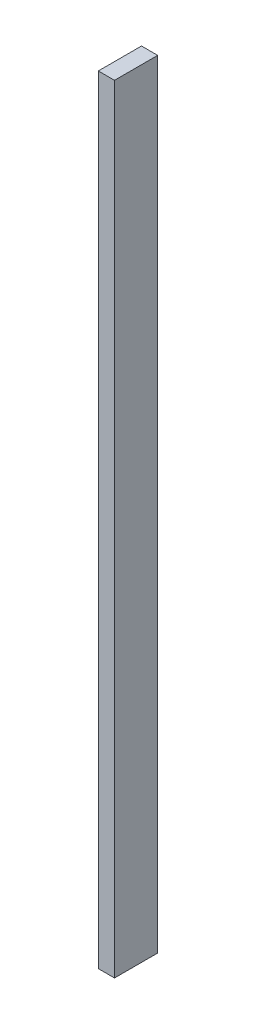
SolidWorks part; units mm, degrees
material "6061-T6 (SS)"
ref_plane "Front Plane" through (0, 0, 0) normal (0, 0, 1) x (1, 0, 0)
ref_plane "Top Plane" through (0, 0, 0) normal (0, 1, 0) x (1, 0, 0)
ref_plane "Right Plane" through (0, 0, 0) normal (1, 0, 0) x (0, 0, -1)
sketch "Sketch1" plane through (0, 0, 0) normal (0, 0, 1) x (1, 0, 0)
  line L1 (0, 0) -> (4.7625, 0)
  line L2 (0, 0) -> (0, 228.6)
  line L3 (0, 228.6) -> (4.7625, 228.6)
  line L4 (4.7625, 0) -> (4.7625, 228.6)
  dimension "D1" = 4.7625
  dimension "D2" = 228.6
extrude "Boss-Extrude1" add sketch "Sketch1" along normal blind 12.7
